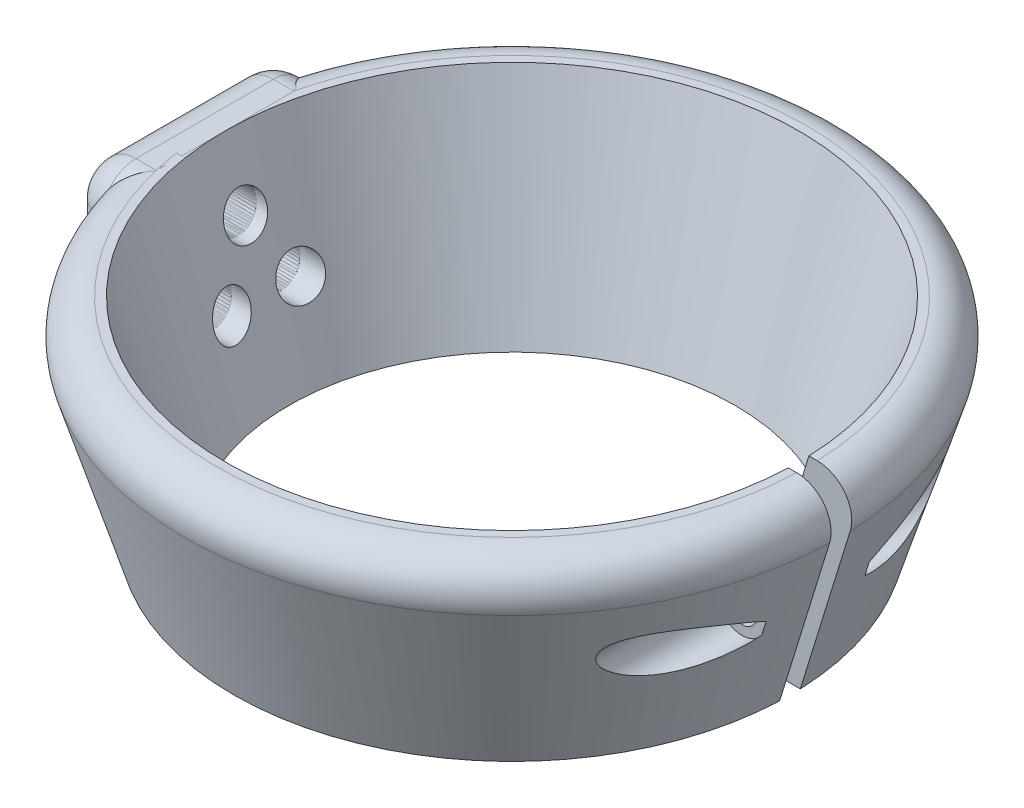
SolidWorks part; units mm, degrees
ref_plane "Front Plane" through (0, 0, 0) normal (0, 0, 1) x (1, 0, 0)
ref_plane "Top Plane" through (0, 0, 0) normal (0, 1, 0) x (1, 0, 0)
ref_plane "Right Plane" through (0, 0, 0) normal (1, 0, 0) x (0, 0, -1)
sketch "Sketch2" plane through (0, 0, 0) normal (1, 0, 0) x (0, 0, -1)
  line L0 (-40.5, -15) -> (-49.75, 15)
  line L1 (-49.75, 15) -> (-41.75, 15)
  line L2 (-41.75, 15) -> (-32.5, -15)
  line L3 (-32.5, -15) -> (-40.5, -15)
  line L4 (0, 0) -> (0, 26.5465) construction
  line L5 (-32.5, -15) -> (0, -15) construction
  line L6 (-41.75, 15) -> (0, 15) construction
  point P7 (-37.125, 0)
  dimension "D1" = 8
  dimension "D2" = 32.5
  dimension "D3" = 41.75
  dimension "D4" = 8
  dimension "D5" = 30
revolve "Revolve1" add sketch "Sketch2" angle 360 mid plane about L4
sketch "Sketch3" plane through (0, 15, 0) normal (0, 1, 0) x (1, 0, 0)
  line L1 (113.6586, -1.5) -> (28.0764, -1.5)
  line L2 (113.6586, -1.5) -> (113.6586, 1.5)
  line L3 (113.6586, 1.5) -> (28.0764, 1.5)
  line L4 (28.0764, -1.5) -> (28.0764, 1.5)
  line L5 (113.6586, -1.5) -> (28.0764, 1.5) construction
  line L6 (113.6586, 1.5) -> (28.0764, -1.5) construction
  point P0 (70.8675, 0)
  dimension "D1" = 3
extrude "Cut-Extrude1" cut sketch "Sketch3" against normal through all
sketch "Sketch4" plane through (0, 0, 0) normal (0, 0, 1) x (1, 0, 0)
  circle A0 centre (41, 0) radius 1.65
  point P2 (36.3446, -15.4023)
  point P3 (36.443, -15.2584)
  point P4 (0, 0)
  point P7 (46.5764, -15.786)
  point P10 (50.2267, 0)
  dimension "D1" = 41
extrude "Cut-Extrude2" cut sketch "Sketch4" against normal through all
ref_plane "Plane1" through (0, 0, -7.5) normal (0, 0, 1) x (1, 0, 0)
sketch "Sketch6" plane through (0, 0, -7.5) normal (0, 0, 1) x (1, 0, 0)
  circle A0 centre (41, 0) radius 3.5
  dimension "D1" = 7
extrude "Cut-Extrude3" cut sketch "Sketch6" against normal through all
mirror "Mirror1" about plane through (0, 0, 0) normal (0, 0, 1) of "Cut-Extrude3"
sketch "Sketch7" plane through (0, 0, 1.5) normal (0, 0, -1) x (-1, 0, 0)
  circle A0 centre (-41, 0) radius 2.125
  dimension "D1" = 4.25
sketch "Sketch8" plane through (0, 0, 0) normal (0, 0, 1) x (1, 0, 0)
  line L0 (-49.75, 15) -> (-49.75, -15)
  line L2 (-49.75, -15) -> (-37.0995, -15)
  line L4 (0, 0) -> (0, 26.5465) construction
  line L5 (0, 0) -> (0, 26.5465) construction
  line L6 (-40.5, -15) -> (40.4722, -15) construction
  line L7 (-37.0995, -15) -> (-41.75, 15)
  line L8 (-41.75, 15) -> (-49.75, 15)
  line L11 (-41.75, 15) -> (-32.5, -15) construction
  point P6 (-43.5809, 15)
  point P8 (-45.0225, 15)
  point P10 (-46.9723, 15)
  point P14 (-40, -15)
  point P17 (-44.7433, 15)
  point P18 (-37.0995, -15)
  point P19 (-42.1741, 15)
  point P20 (-41.9252, 15)
  point P21 (-41.7357, 15)
  point P22 (-41.9132, 15)
  point P23 (-41.8428, 15)
  point P25 (-41.7457, 15)
  point P26 (-41.75, 15)
  point P29 (-41.75, 15)
extrude "Boss-Extrude1" add sketch "Sketch8" along normal mid plane 30 separate body
sketch "Sketch9" plane through (-49.75, 0, 0) normal (-1, 0, 0) x (0, 0, 1)
  line L0 (0, 0) -> (0, 26.5465) construction
  line L1 (0, 5.7735) -> (-5, -2.8868) construction
  line L2 (-5, -2.8868) -> (5, -2.8868) construction
  line L3 (5, -2.8868) -> (0, 5.7735) construction
  line L4 (-2.5, 1.4434) -> (5, -2.8868) construction
  line L5 (5, -2.8868) -> (2.5, 1.4434) construction
  line L6 (2.5, 1.4434) -> (-5, -2.8868) construction
  line L7 (15, 15) -> (15, -15) construction
  circle A0 centre (0, 5.7735) radius 1.65
  circle A1 centre (5, -2.8868) radius 1.65
  circle A2 centre (-5, -2.8868) radius 1.65
  point P13 (0, 0)
  point P21 (15, 0)
  dimension "D2" = 3.3
  dimension "D1" = 10
extrude "Cut-Extrude5" cut sketch "Sketch9" against normal blind 30
sketch "Sketch10" plane through (0, 0, 0) normal (1, 0, 0) x (0, 0, -1)
  circle A0 centre (5, -2.8868) radius 3.075
  circle A1 centre (-5, -2.8868) radius 3.075
  circle A2 centre (0, 5.7735) radius 3.075
  dimension "D1" = 6.15
extrude "Cut-Extrude6" cut sketch "Sketch10" against normal blind 46
fillet "Fillet1" [suppressed] radius 5
fillet "Fillet2" radius 5 5 edges at (-45.75, 15, 15) (-45.75, 15, -15) (-49.75, 0, -15) (-49.75, 0, 15) (-49.75, 15, 0)
fillet "Fillet3" radius 5 1 edges at (-49.75, 15, 0)
extrude "Cut-Extrude8" cut sketch "Sketch7" against normal through all
